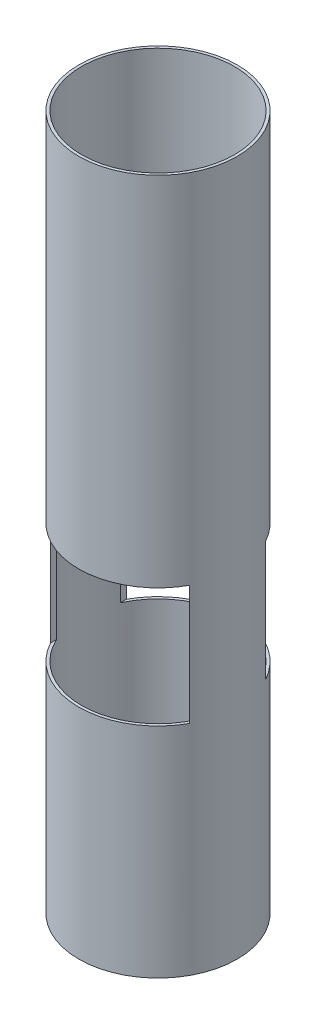
SolidWorks part; units mm, degrees
ref_plane "Front Plane" through (0, 0, 0) normal (0, 0, 1) x (1, 0, 0)
ref_plane "Top Plane" through (0, 0, 0) normal (0, 1, 0) x (1, 0, 0)
ref_plane "Right Plane" through (0, 0, 0) normal (1, 0, 0) x (0, 0, -1)
sketch "Sketch1" plane through (0, 0, 0) normal (0, 1, 0) x (1, 0, 0)
  circle A0 centre (0, 0) radius 55
  circle A1 centre (0, 0) radius 57
  dimension "D1" = 110
  dimension "D2" = 2
extrude "Boss-Extrude1" add sketch "Sketch1" along normal blind 500
sketch "Sketch2" plane through (-168.9329, 99.4365, -468.1144) normal (0, 0, 1) x (1, 0, 0)
  line L0 (111.9329, 400.5635) -> (111.9329, -99.4365) construction
  line L1 (111.9329, 150.5635) -> (225.9329, 150.5635) construction
  line L2 (111.9329, 150.5635) -> (111.9329, 50.5635) construction
  line L3 (111.9329, 50.5635) -> (225.9329, 50.5635) construction
  line L4 (225.9329, 150.5635) -> (225.9329, 50.5635) construction
  line L5 (225.9329, -99.4365) -> (225.9329, 400.5635) construction
  line L6 (118.9329, 143.5635) -> (118.9329, 57.5635)
  line L7 (118.9329, 57.5635) -> (218.9329, 57.5635)
  line L8 (218.9329, 143.5635) -> (218.9329, 57.5635)
  line L9 (118.9329, 143.5635) -> (218.9329, 143.5635)
  line L10 (111.9329, -99.4365) -> (225.9329, -99.4365) construction
  dimension "D2" = 250
  dimension "D3" = 100
  dimension "D1" = 7
extrude "Cut-Extrude2" cut sketch "Sketch2" against normal through all both and the other way through all
